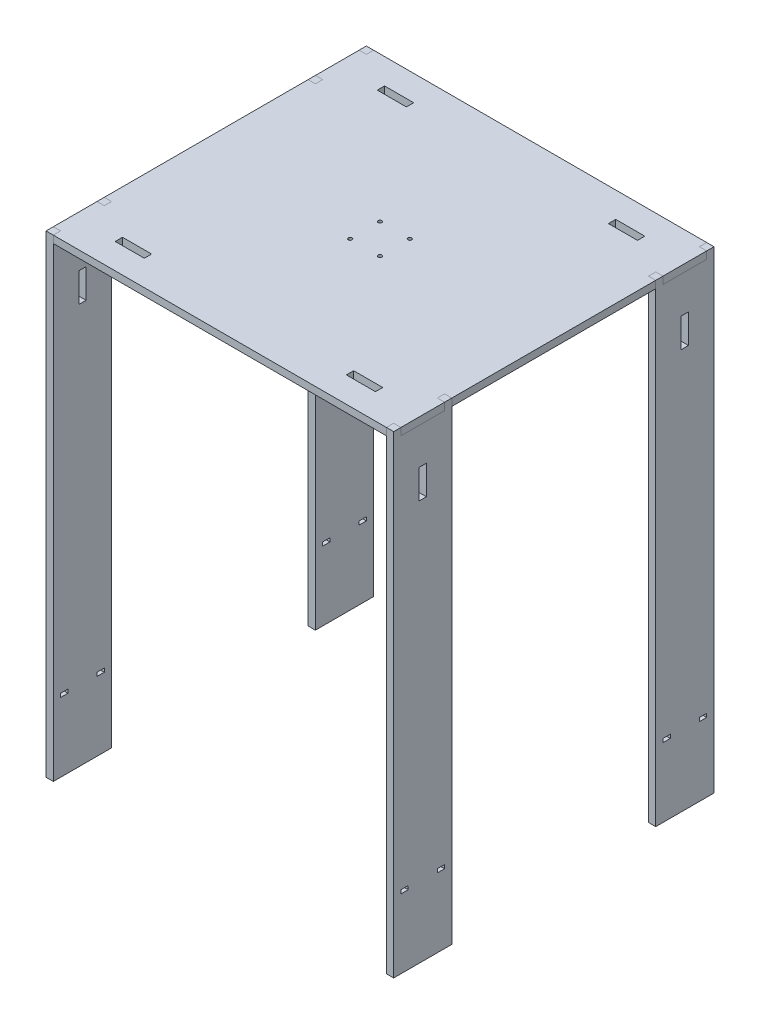
SolidWorks part; units mm, degrees
material "Beech"
ref_plane "Front Plane" through (0, 0, 0) normal (0, 0, 1) x (1, 0, 0)
ref_plane "Top Plane" through (0, 0, 0) normal (0, 1, 0) x (1, 0, 0)
ref_plane "Right Plane" through (0, 0, 0) normal (1, 0, 0) x (0, 0, -1)
sketch "Sketch1" plane through (0, 0, 0) normal (0, 1, 0) x (1, 0, 0)
  line L0 (145.2562, 0) -> (-145.2562, 0) construction
  line L1 (-145.2562, 0) -> (-151.6062, 0) construction
  line L2 (0, 0) -> (0, 36.9734) construction
  line L3 (-145.2562, -25.4) -> (-151.6063, -25.4)
  line L4 (-145.2562, -25.4) -> (-145.2562, 25.4)
  line L5 (-145.2562, 25.4) -> (-151.6063, 25.4)
  line L6 (-151.6063, -25.4) -> (-151.6063, 25.4)
  line L7 (-145.2562, -25.4) -> (-151.6063, 25.4) construction
  line L8 (-145.2562, 25.4) -> (-151.6063, -25.4) construction
  line L9 (145.2562, 25.4) -> (151.6063, 25.4)
  line L10 (151.6063, -25.4) -> (151.6063, 25.4)
  line L11 (145.2562, -25.4) -> (151.6063, -25.4)
  line L12 (145.2562, -25.4) -> (145.2562, 25.4)
  point P0 (-148.4313, 0)
  point P4 (0, 0)
  dimension "D1" = 290.5125
  dimension "D2" = 6.35
  dimension "D3" = 50.8
extrude "Boss-Extrude1" add sketch "Sketch1" along normal blind 412.75
sketch "Sketch3" plane through (151.6063, 0, 0) normal (1, 0, 0) x (0, 0, -1)
  line L0 (0, 412.75) -> (0, 409.575) construction
  line L1 (-25.4, 412.75) -> (25.4, 412.75) construction
  line L2 (-25.4, 412.75) -> (-25.4, 0) construction
  line L3 (19.05, 406.4) -> (-19.05, 406.4)
  line L4 (19.05, 406.4) -> (19.05, 412.75)
  line L5 (19.05, 412.75) -> (-19.05, 412.75)
  line L6 (-19.05, 406.4) -> (-19.05, 412.75)
  line L7 (19.05, 406.4) -> (-19.05, 412.75) construction
  line L8 (19.05, 412.75) -> (-19.05, 406.4) construction
  line L9 (0, 406.4) -> (0, 63.5) construction
  line L10 (0, 63.5) -> (-19.05, 63.5) construction
  line L11 (19.05, 60.325) -> (12.7, 60.325)
  line L12 (-19.05, 63.5) -> (-12.7, 63.5)
  line L13 (-19.05, 63.5) -> (-19.05, 60.325)
  line L14 (-19.05, 60.325) -> (-12.7, 60.325)
  line L15 (-12.7, 63.5) -> (-12.7, 60.325)
  line L16 (12.7, 63.5) -> (12.7, 60.325)
  line L17 (19.05, 63.5) -> (12.7, 63.5)
  line L18 (19.05, 63.5) -> (19.05, 60.325)
  dimension "D1" = 3.175
  dimension "D2" = 6.35
  dimension "D3" = 342.9
  dimension "D4" = 6.35
  dimension "D5" = 6.35
  dimension "D6" = 3.175
extrude "Cut-Extrude1" cut sketch "Sketch3" against normal through all
sketch "Sketch4" plane through (0, 412.75, 0) normal (0, 1, 0) x (1, 0, 0)
  line L1 (-145.2562, 19.05) -> (-151.6063, 19.05)
  line L2 (-145.2562, 19.05) -> (-145.2562, -19.05)
  line L3 (-145.2562, -19.05) -> (-151.6063, -19.05)
  line L4 (-151.6063, 19.05) -> (-151.6063, -19.05)
  line L5 (151.6063, 19.05) -> (145.2562, 19.05)
  line L6 (151.6063, 19.05) -> (151.6063, -19.05)
  line L7 (151.6063, -19.05) -> (145.2562, -19.05)
  line L8 (145.2562, 19.05) -> (145.2562, -19.05)
  line L9 (145.2562, 25.4) -> (-145.2562, 25.4)
  line L10 (145.2562, 25.4) -> (145.2562, -25.4)
  line L11 (145.2562, -25.4) -> (-145.2562, -25.4)
  line L12 (-145.2562, 25.4) -> (-145.2562, -25.4)
  line M1 (-151.6063, 19.05) -> (-145.2562, 19.05)
  line M2 (-145.2562, 19.05) -> (-145.2562, 25.4)
extrude "Boss-Extrude2" add sketch "Sketch4" against normal blind 6.35 separate body contours L4 L3 L2 M1 | L2 L12 L11 L10 L8 L9 M2 | L5 L8 L7 L6
sketch "Sketch5" plane through (0, 0, 0) normal (0, 1, 0) x (1, 0, 0)
  line L0 (151.6063, 25.4) -> (151.6063, 203.2) construction
  line L1 (151.6063, 114.3) -> (35.7143, 114.3) construction
  dimension "D1" = 177.8
ref_plane "Plane1" through (0, 0, -114.3) normal (0, 0, -1) x (-1, 0, 0)
mirror "Mirror6" about plane through (0, 0, -114.3) normal (0, 0, -1) of bodies 105 104 103
sketch "Sketch8" plane through (0, 412.75, 0) normal (0, 1, 0) x (1, 0, 0)
  line L1 (-151.6063, 203.2) -> (151.6063, 203.2)
  line L2 (-151.6063, 203.2) -> (-151.6063, 25.4)
  line L3 (-151.6063, 25.4) -> (151.6063, 25.4)
  line L4 (151.6063, 203.2) -> (151.6063, 25.4)
extrude "Boss-Extrude5" add sketch "Sketch8" against normal blind 6.35
sketch "Sketch9" plane through (0, 412.75, 0) normal (0, 1, 0) x (1, 0, 0)
  line L0 (-151.6063, 114.3) -> (151.6063, 114.3) construction
  line L1 (-151.6063, 203.2) -> (-151.6063, 25.4) construction
  line L2 (151.6063, 25.4) -> (151.6063, 203.2) construction
  line L3 (0, 254) -> (0, -25.4) construction
  line L4 (145.2562, 254) -> (-145.2562, 254) construction
  line L5 (145.2562, -25.4) -> (-145.2562, -25.4) construction
  line L6 (0, 254) -> (0, 228.6) construction
  line L7 (13, 101.3) -> (-13, 101.3) construction
  line L8 (13, 101.3) -> (13, 127.3) construction
  line L9 (13, 127.3) -> (-13, 127.3) construction
  line L10 (-13, 101.3) -> (-13, 127.3) construction
  line L11 (13, 101.3) -> (-13, 127.3) construction
  line L12 (13, 127.3) -> (-13, 101.3) construction
  line L13 (18.7789, 228.6) -> (-18.7789, 228.6) construction
  point P12 (0, 114.3)
  point P13 (0, 114.3)
  point P19 (-13, 127.3)
  point P20 (13, 127.3)
  point P21 (13, 101.3)
  point P22 (-13, 101.3)
  point P25 (0, 228.6)
  dimension "D1" = 26
  dimension "D2" = 25.4
hole_wizard "M3 Clearance Hole1" positions "Sketch10" profile "Sketch11" hole size "M3" standard "ANSI Metric" end condition through all
sketch "Sketch10" plane through (0, 412.75, 0) normal (0, 1, 0) x (1, 0, 0)
  point P0 (-13, 101.3)
  point P3 (-13, 127.3)
  point P6 (13, 127.3)
  point P9 (13, 101.3)
sketch "Sketch11" plane through (-13, 412.75, -101.3) normal (1, 0, 0) x (0, 0, 1)
  line L0 (0, 0) -> (0, 412.75)
  line L1 (0, 412.75) -> (1.6, 412.75)
  line L2 (1.6, 412.75) -> (1.6, 0)
  line L5 (1.6, 0) -> (0, 0)
  line L11 (0, -6.35) -> (0, 107.95) construction
  dimension "Thru Hole Dia." = 3.2
  dimension "Thru Hole Depth" = 412.75
sketch "Sketch12" plane through (0, 412.75, 0) normal (0, 1, 0) x (1, 0, 0)
  line L0 (-151.6063, 0) -> (-100.8063, 0) construction
  line L1 (-151.6063, 19.05) -> (-151.6063, -19.05) construction
  line L2 (0, -25.4) -> (0, 254) construction
  line L3 (-113.5063, -3.175) -> (-88.1063, -3.175)
  line L4 (-113.5063, -3.175) -> (-113.5063, 3.175)
  line L5 (-113.5063, 3.175) -> (-88.1063, 3.175)
  line L6 (-88.1063, -3.175) -> (-88.1063, 3.175)
  line L7 (-113.5063, -3.175) -> (-88.1063, 3.175) construction
  line L8 (-113.5063, 3.175) -> (-88.1063, -3.175) construction
  line L9 (145.2562, -25.4) -> (-145.2562, -25.4) construction
  line L10 (145.2562, 254) -> (-145.2562, 254) construction
  line L11 (-151.6063, 114.3) -> (151.6063, 114.3) construction
  line L12 (-151.6063, 203.2) -> (-151.6063, 25.4) construction
  line L13 (151.6063, 25.4) -> (151.6063, 203.2) construction
  line L14 (113.5063, 3.175) -> (88.1063, 3.175)
  line L15 (88.1063, -3.175) -> (88.1063, 3.175)
  line L16 (113.5063, -3.175) -> (88.1063, -3.175)
  line L17 (113.5063, -3.175) -> (113.5063, 3.175)
  line L18 (113.5063, 231.775) -> (113.5063, 225.425)
  line L19 (113.5063, 231.775) -> (88.1063, 231.775)
  line L20 (88.1063, 231.775) -> (88.1063, 225.425)
  line L21 (113.5063, 225.425) -> (88.1063, 225.425)
  line L22 (-113.5063, 225.425) -> (-88.1063, 225.425)
  line L23 (-88.1063, 231.775) -> (-88.1063, 225.425)
  line L24 (-113.5063, 231.775) -> (-88.1063, 231.775)
  line L25 (-113.5063, 231.775) -> (-113.5063, 225.425)
  dimension "D1" = 50.8
  dimension "D2" = 6.35
  dimension "D3" = 25.4
extrude "Cut-Extrude2" cut sketch "Sketch12" against normal up to next (6.35 mm away)
sketch "Sketch13" plane through (-151.6063, 0, 0) normal (-1, 0, 0) x (0, 0, 1)
  line L0 (-228.6, 412.75) -> (-228.6, 361.95) construction
  line L1 (-209.55, 412.75) -> (-247.65, 412.75) construction
  line L2 (-114.3, 412.75) -> (-114.3, 406.4)
  line L3 (-225.425, 349.25) -> (-231.775, 349.25)
  line L4 (-225.425, 349.25) -> (-225.425, 374.65)
  line L5 (-225.425, 374.65) -> (-231.775, 374.65)
  line L6 (-231.775, 349.25) -> (-231.775, 374.65)
  line L7 (-225.425, 349.25) -> (-231.775, 374.65) construction
  line L8 (-225.425, 374.65) -> (-231.775, 349.25) construction
  line L9 (-203.2, 412.75) -> (-25.4, 412.75) construction
  line L10 (-203.2, 406.4) -> (-25.4, 406.4) construction
  line L11 (-3.175, 374.65) -> (3.175, 374.65)
  line L12 (3.175, 349.25) -> (3.175, 374.65)
  line L13 (-3.175, 349.25) -> (3.175, 349.25)
  line L14 (-3.175, 349.25) -> (-3.175, 374.65)
  dimension "D1" = 6.35
  dimension "D2" = 25.4
  dimension "D3" = 50.8
extrude "Cut-Extrude3" cut sketch "Sketch13" against normal blind 6.35 contours L6 L3 L4 L5 | L14 L13 L12 L11
mirror "Mirror7" about plane through (0, 0, 0) normal (1, 0, 0) of "Cut-Extrude3"
